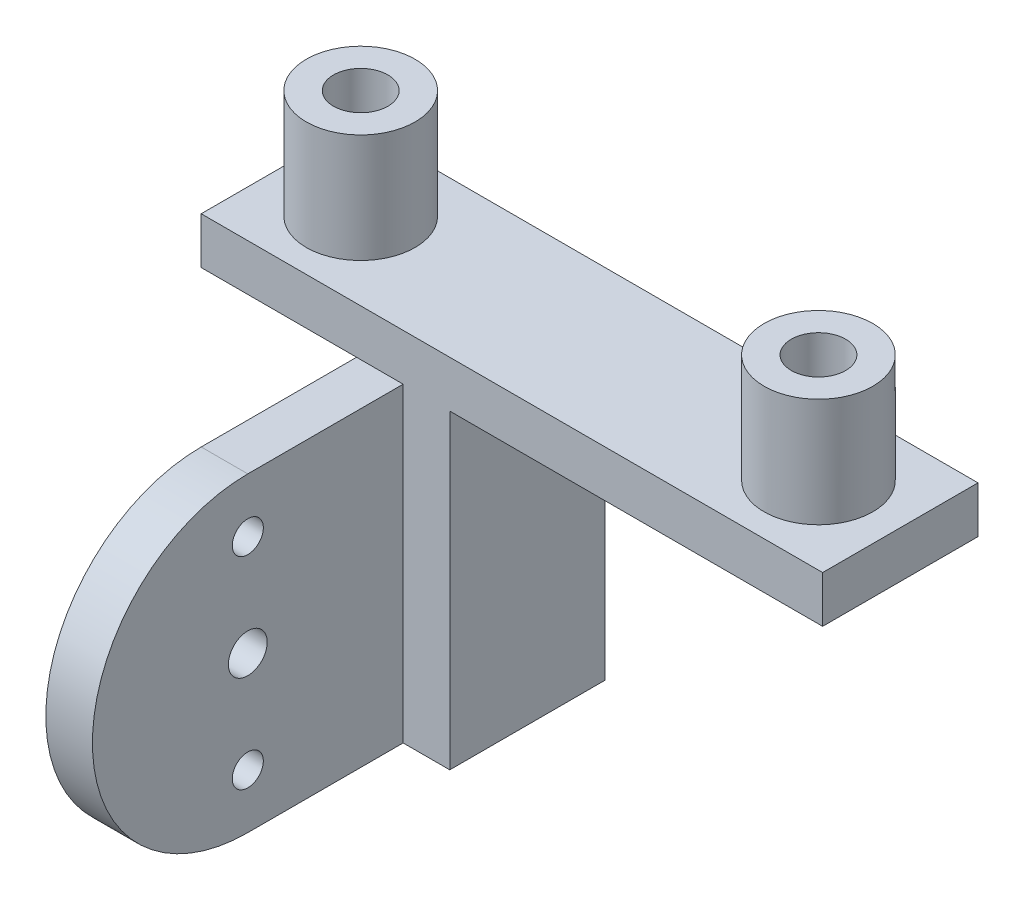
SolidWorks part; units mm, degrees
ref_plane "前视基准面" through (0, 0, 0) normal (0, 0, 1) x (1, 0, 0)
ref_plane "上视基准面" through (0, 0, 0) normal (0, 1, 0) x (1, 0, 0)
ref_plane "右视基准面" through (0, 0, 0) normal (1, 0, 0) x (0, 0, -1)
sketch "草图1" plane through (0, 0, 0) normal (0, 1, 0) x (1, 0, 0)
  line L0 (14.732, 0) -> (-14.732, 0) construction
  line L1 (20, 5) -> (-20, 5)
  line L2 (20, 5) -> (20, -5)
  line L3 (20, -5) -> (-20, -5)
  line L4 (-20, 5) -> (-20, -5)
  line L5 (20, 5) -> (-20, -5) construction
  line L6 (20, -5) -> (-20, 5) construction
  circle A0 centre (-14.732, 0) radius 1.75
  circle A1 centre (14.732, 0) radius 1.75
  point P0 (0, 0)
  point P9 (0, 0)
  dimension "D4" = 3.5
  dimension "D5" = 3.5
  dimension "D1" = 10
  dimension "D2" = 40
  dimension "D3" = 29.464
extrude "凸台-拉伸1" add sketch "草图1" along normal blind 3
sketch "草图2" plane through (0, 0, 0) normal (1, 0, 0) x (0, 0, -1)
  line L0 (-15, -16.5) -> (-15, -3.5) construction
  line L6 (5, 0) -> (-15, 0)
  line L7 (5, 0) -> (5, -20)
  line L8 (5, -20) -> (-15, -20)
  line L9 (-15, 0) -> (-15, -20) construction
  arc A2 (-15, 0) -> (-15, -20) centre (-15, -10) ccw
  circle A4 centre (-15, -3.5) radius 1
  circle A5 centre (-15, -16.5) radius 1
  circle A6 centre (-15, -10) radius 1.25
  point P7 (-15, -10)
  dimension "D2" = 20
  dimension "D3" = 13
  dimension "D4" = 2
  dimension "D5" = 2
  dimension "D1" = 20
extrude "凸台-拉伸2" add sketch "草图2" along normal blind 3 from offset 10 offset against normal yes
sketch "草图3" plane through (0, 0, 0) normal (0, -1, 0) x (1, 0, 0)
  line L0 (-7, 15) -> (-7, -5) construction
  line L1 (-7, 5) -> (-4, 5)
  line L2 (-7, 5) -> (-7, -5)
  line L3 (-7, -5) -> (-4, -5)
  line L4 (-4, 5) -> (-4, -5)
  line L5 (20, -5) -> (-7, -5) construction
  dimension "D1" = 3
extrude "凸台-拉伸3" add sketch "草图3" along normal up to surface (20 mm away) up to face at (-8.5, -20, 5)
sketch "草图4" plane through (0, 3, 0) normal (0, 1, 0) x (1, 0, 0)
  circle A0 centre (14.732, 0) radius 1.75 construction
  circle A1 centre (-14.732, 0) radius 1.75 construction
  circle A2 centre (14.732, 0) radius 1.75
  circle A3 centre (-14.732, 0) radius 1.75
  circle A4 centre (-14.732, 0) radius 3.5
  circle A5 centre (14.732, 0) radius 3.5
  dimension "D1" = 7
  dimension "D2" = 7
extrude "凸台-拉伸4" add sketch "草图4" along normal blind 7
